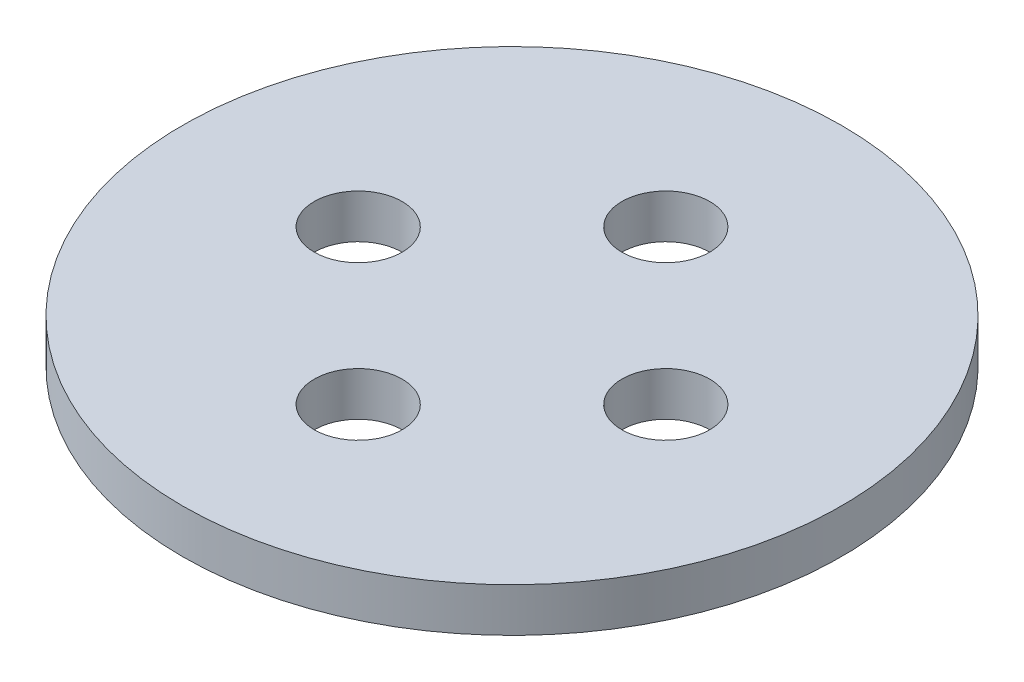
SolidWorks part; units mm, degrees
ref_plane "Front Plane" through (0, 0, 0) normal (0, 0, 1) x (1, 0, 0)
ref_plane "Top Plane" through (0, 0, 0) normal (0, 1, 0) x (1, 0, 0)
ref_plane "Right Plane" through (0, 0, 0) normal (1, 0, 0) x (0, 0, -1)
sketch "Sketch1" plane through (0, 0, 0) normal (0, 1, 0) x (1, 0, 0)
  circle A0 centre (0, 0) radius 15
  circle A1 centre (0, 0) radius 7 construction
  circle A2 centre (0, 7) radius 2
  circle A3 centre (7, 0) radius 2
  circle A4 centre (0, -7) radius 2
  circle A5 centre (-7, 0) radius 2
  point P15 (0, 0)
  dimension "D1" = 30
  dimension "D2" = 14
  dimension "D3" = 4
  dimension "D4" = 4
extrude "Boss-Extrude1" add sketch "Sketch1" along normal blind 2
